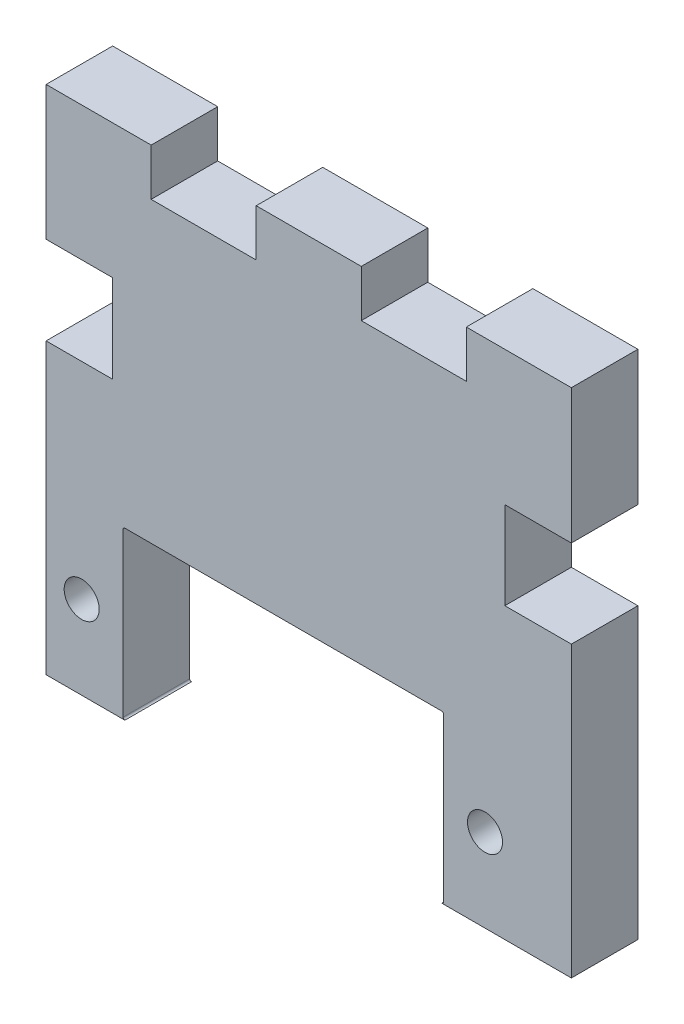
SolidWorks part; units mm, degrees
ref_plane "Front Plane" through (0, 0, 0) normal (0, 0, 1) x (1, 0, 0)
ref_plane "Top Plane" through (0, 0, 0) normal (0, 1, 0) x (1, 0, 0)
ref_plane "Right Plane" through (0, 0, 0) normal (1, 0, 0) x (0, 0, -1)
sketch "Sketch1" plane through (0, 0, 0) normal (0, 0, 1) x (1, 0, 0)
  line L1 (0, 0) -> (38.1, 0)
  line L2 (0, 0) -> (0, 37.084)
  line L3 (0, 37.084) -> (38.1, 37.084)
  line L4 (38.1, 0) -> (38.1, 37.084)
  dimension "D1" = 38.1
  dimension "D2" = 37.084
extrude "Boss-Extrude1" add sketch "Sketch1" along normal blind 4.826
sketch "Sketch3" plane through (0, 0, 4.826) normal (0, 0, 1) x (1, 0, 0)
  circle A2 centre (2.5805, 6.0325) radius 1.27
  circle A3 centre (31.8365, 6.0325) radius 1.27
extrude "Cut-Extrude2" cut sketch "Sketch3" against normal through all
sketch "Sketch4" plane through (0, 0, 0) normal (0, 0, -1) x (-1, 0, 0)
  line L0 (-28.702, 12.065) -> (-5.715, 12.065) construction
  line L1 (-28.829, 0.127) -> (-28.829, 11.938) construction
  line L2 (-5.588, 11.938) -> (-5.588, 0.127) construction
  line L3 (-5.715, 0) -> (-28.702, 0) construction
  line L4 (-28.702, 12.065) -> (-5.715, 12.065)
  line L5 (-28.829, 0.127) -> (-28.829, 11.938)
  line L6 (-5.588, 11.938) -> (-5.588, 0.127)
  line L7 (-5.715, 0) -> (-28.702, 0)
  arc A0 (-5.715, 0) -> (-5.588, 0.127) centre (-5.715, 0.127) ccw construction
  arc A1 (-28.829, 0.127) -> (-28.702, 0) centre (-28.702, 0.127) ccw construction
  arc A2 (-28.702, 12.065) -> (-28.829, 11.938) centre (-28.702, 11.938) ccw construction
  arc A3 (-5.588, 11.938) -> (-5.715, 12.065) centre (-5.715, 11.938) ccw construction
  arc A4 (-5.715, 0) -> (-5.588, 0.127) centre (-5.715, 0.127) ccw
  arc A5 (-28.829, 0.127) -> (-28.702, 0) centre (-28.702, 0.127) ccw
  arc A6 (-28.702, 12.065) -> (-28.829, 11.938) centre (-28.702, 11.938) ccw
  arc A7 (-5.588, 11.938) -> (-5.715, 12.065) centre (-5.715, 11.938) ccw
extrude "Cut-Extrude3" cut sketch "Sketch4" against normal through all
sketch "Sketch5" plane through (0, 0, 4.826) normal (0, 0, 1) x (1, 0, 0)
  line L0 (38.1, 37.084) -> (0, 37.084) construction
  line L1 (7.62, 37.084) -> (15.24, 37.084)
  line L2 (7.62, 37.084) -> (7.62, 33.6741)
  line L3 (7.62, 33.6741) -> (15.24, 33.6741)
  line L4 (15.24, 37.084) -> (15.24, 33.6741)
  line L5 (0, 33.6741) -> (7.62, 33.6741) construction
  line L6 (22.86, 37.084) -> (30.48, 37.084)
  line L7 (22.86, 37.084) -> (22.86, 33.6741)
  line L8 (22.86, 33.6741) -> (30.48, 33.6741)
  line L9 (30.48, 37.084) -> (30.48, 33.6741)
  line L10 (0, 37.084) -> (0, 0) construction
  line L11 (15.24, 33.6741) -> (22.86, 33.6741) construction
  line L12 (30.48, 33.6741) -> (38.1, 33.6741) construction
  line L13 (38.1, 0) -> (38.1, 37.084) construction
extrude "Cut-Extrude4" cut sketch "Sketch5" against normal through all
sketch "Sketch7" plane through (0, 0, 4.826) normal (0, 0, 1) x (1, 0, 0)
  line L0 (0, 37.084) -> (0, 0) construction
  line L1 (0, 27.3545) -> (4.826, 27.3545)
  line L2 (0, 27.3545) -> (0, 20.9741)
  line L3 (0, 20.9741) -> (4.826, 20.9741)
  line L4 (4.826, 27.3545) -> (4.826, 20.9741)
  line L5 (38.1, 0) -> (38.1, 37.084) construction
  line L6 (33.274, 27.3241) -> (38.1, 27.3241)
  line L7 (33.274, 27.3241) -> (33.274, 20.9741)
  line L8 (33.274, 20.9741) -> (38.1, 20.9741)
  line L9 (38.1, 27.3241) -> (38.1, 20.9741)
extrude "Cut-Extrude5" cut sketch "Sketch7" against normal through all
equation "\"MDF\"= 0.19in"
equation "\"PVCID\" = 2.067in"
equation "\"PVCOD\" = 2.375in"
equation "\"GenDiameter\"= 60mm"
equation "\"GenCutDiameter\" = 1.8in"
equation "\"GenCutDistance\" = 1"
equation "\"TowerHeight\" = 6in"
equation "\"TowerFrontBase\" = 3in"
equation "\"FunnelHeight\" = 1in"
equation "\"FunnelAngle\" = 20"
equation "\"TowerSideBase\" = 3in"
equation "\"TowerPanelLength\" = 2in"
equation "\"TowerPanelLeeway\" = 0.5in"
equation "\"BaseLength\" = 9in"
equation "\"BaseWidth\" = 10in"
equation "\"WheelHoleLength\" = 3.25in"
equation "\"WheelHoleWidth\" = 26mm"
equation "\"WheelHoleFromBack\" = 1.5in"
equation "\"DropLength\" = 1in"
equation "\"DropWidth\" = 8.5in"
equation "\"BumperWidth\" = 2in"
equation "\"SmallHexDiameter\" = 0.185in"
equation "\"SmallHexHeight\" = 0.701in"
equation "\"ScrewSize\" = 0.106in"
equation "\"BigHexDiameter\" = 0.251in"
equation "\"BigHexHeight\" = 0.374in"
equation "\"PCBThickness\" = 0.066in"
equation "\"ConnectorHeight\" = 0.517in"
equation "\"BoardHeight\" = 0.583in"
equation "\"UnoStackHeight\" = 1.351in"
equation "\"UnoStackWidth\" = 3.053in"
equation "\"UnoStackLength\" = 3.152in"
equation "\"HBridgeWidth\" = 1.797in"
equation "\"HBridgeLength\" = 2.236in"
equation "\"DSWidth\" = 1.820in"
equation "\"DSLength\" = 1.833in"
equation "\"StepperWidth\" = 1.799in"
equation "\"StepperLength\" = 2.248in"
equation "\"ULNWidth\" = 1.304in"
equation "\"ULNLength\" = 1.545in"
equation "\"VSwitchHeight\" = 0.392in"
equation "\"VSwitchWidth\" = 0.637in"
equation "\"VSwitchLength\" = 1.097in"
equation "\"SkateWheelDiameter\" = 80mm"
equation "\"SkateWheelThickness\" = 24mm"
equation "\"BaseDistance\" = 3in"
equation "\"DummyVar\" = 2in"
equation "\"D1@Boss-Extrude1\"=\"MDF\""
equation "\"D2@Sketch1\"=\"MDF\"+1.27in"
